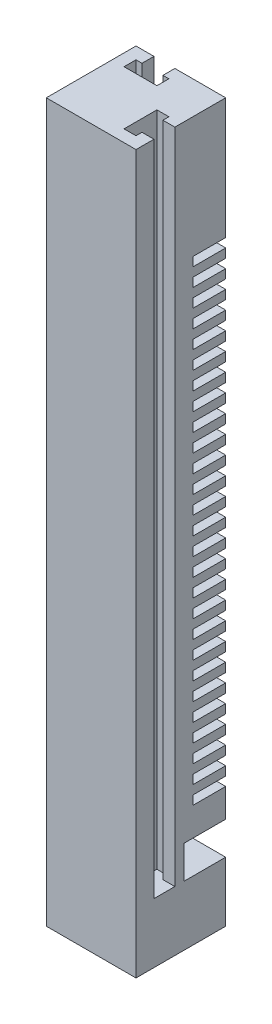
SolidWorks part; units mm, degrees
material "Alumina"
ref_plane "Front Plane" through (0, 0, 0) normal (0, 0, 1) x (1, 0, 0)
ref_plane "Top Plane" through (0, 0, 0) normal (0, 1, 0) x (1, 0, 0)
ref_plane "Right Plane" through (0, 0, 0) normal (1, 0, 0) x (0, 0, -1)
sketch "Sketch1" plane through (0, 0, 0) normal (0, 1, 0) x (1, 0, 0)
  line L1 (0, 0) -> (15, 0)
  line L2 (0, 0) -> (0, 15)
  line L3 (0, 15) -> (15, 15)
  line L4 (15, 0) -> (15, 15)
  dimension "D1" = 15
  dimension "D2" = 15
extrude "Boss-Extrude1" add sketch "Sketch1" along normal blind 120
sketch "Sketch3" plane through (0, 120, 0) normal (0, 1, 0) x (1, 0, 0)
  line L0 (15, 3) -> (13, 3)
  line L1 (15, 0) -> (15, 15) construction
  line L2 (13, 3) -> (13, 2)
  line L3 (13, 2) -> (11, 2)
  line L4 (11, 2) -> (11, 7.5)
  line L5 (11, 7.5) -> (13, 7.5)
  line L6 (13, 7.5) -> (13, 6.5)
  line L7 (13, 6.5) -> (15, 6.5)
  line L8 (15, 6.5) -> (15, 3)
  line L9 (15, 15) -> (0, 0) construction
  line L10 (3, 13) -> (2, 13)
  line L11 (6.5, 15) -> (3, 15)
  line L12 (7.5, 13) -> (6.5, 13)
  line L13 (6.5, 13) -> (6.5, 15)
  line L14 (7.5, 11) -> (7.5, 13)
  line L15 (2, 11) -> (7.5, 11)
  line L16 (2, 13) -> (2, 11)
  line L17 (3, 15) -> (3, 13)
  dimension "D1" = 3
  dimension "D2" = 5.5
  dimension "D3" = 3.5
  dimension "D4" = 1
  dimension "D5" = 2
  dimension "D6" = 2
extrude "Cut-Extrude1" cut sketch "Sketch3" against normal blind 110
sketch "Sketch5" plane through (0, 120, 0) normal (0, 1, 0) x (1, 0, 0)
  line L0 (15, 15) -> (15, 9.5)
  line L2 (15, 9.5) -> (9.5, 15)
  line L4 (9.5, 15) -> (15, 15)
  dimension "D1" = 5.5
  dimension "D2" = 5.5
extrude "Cut-Extrude2" cut sketch "Sketch5" against normal blind 1.5 from offset 20.25 offset against normal yes
pattern_linear "LPattern1" count 27 spacing 3 along (0, -1, 0) of "Cut-Extrude2"
sketch "Sketch6" plane through (0, 0, 0) normal (0, -1, 0) x (1, 0, 0)
  line L5 (15, -15) -> (8, -15)
  line L9 (15, -8) -> (15, -15)
  line L10 (8, -15) -> (8, -8)
  line L11 (8, -8) -> (15, -8)
  dimension "D1" = 7
  dimension "D2" = 7
extrude "Cut-Extrude3" cut sketch "Sketch6" against normal blind 5.5 from offset 10
